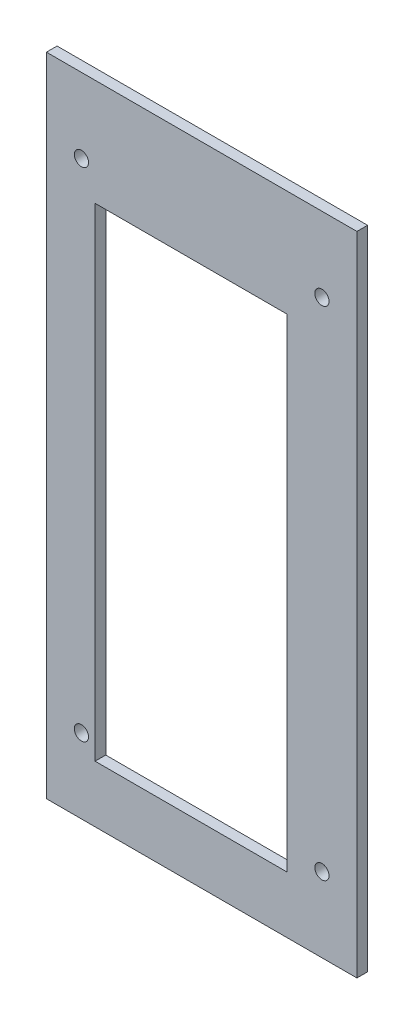
SolidWorks part; units mm, degrees
ref_plane "Front Plane" through (0, 0, 0) normal (0, 0, 1) x (1, 0, 0)
ref_plane "Top Plane" through (0, 0, 0) normal (0, 1, 0) x (1, 0, 0)
ref_plane "Right Plane" through (0, 0, 0) normal (1, 0, 0) x (0, 0, -1)
sketch "Sketch1" plane through (0, 0, 0) normal (0, 0, 1) x (1, 0, 0)
  line L0 (-16.925, 45.5) -> (-16.925, -45.5) construction
  line L1 (-21.85, 45.5) -> (21.85, 45.5)
  line L2 (-21.85, 45.5) -> (-21.85, -45.5)
  line L3 (-21.85, -45.5) -> (21.85, -45.5)
  line L4 (21.85, 45.5) -> (21.85, -45.5)
  line L5 (-21.85, 45.5) -> (21.85, -45.5) construction
  line L6 (-21.85, -45.5) -> (21.85, 45.5) construction
  line L7 (16.925, 45.5) -> (16.925, -45.5) construction
  line L8 (-15, 45.5) -> (-15, -45.5) construction
  line L9 (-15, 30.5) -> (12, 30.5)
  line L10 (-15, 30.5) -> (-15, -37.5)
  line L11 (-15, -37.5) -> (12, -37.5)
  line L12 (12, 30.5) -> (12, -37.5)
  line L13 (-18.85, -45.5) -> (-18.85, 45.5) construction
  line L14 (15, 45.5) -> (15, -45.5) construction
  line L15 (18.85, -45.5) -> (18.85, 45.5) construction
  line L16 (-21, 11.5) -> (21, 11.5) construction
  line L17 (-21.85, 0) -> (21.85, 0) construction
  line L18 (0, 45.5) -> (0, -45.5) construction
  circle A0 centre (16.925, 35) radius 1
  circle A1 centre (16.925, -35) radius 1
  circle A2 centre (-16.925, 35) radius 1
  circle A3 centre (-16.925, -35) radius 1
  point P0 (0, 0)
  dimension "D7" = 2
  dimension "D8" = 70
  dimension "D9" = 70
  dimension "D14" = 35
  dimension "D2" = 27
  dimension "D3" = 3
  dimension "D4" = 3
  dimension "D5" = 43.7
  dimension "D6" = 3
  dimension "D10" = 3.85
  dimension "D11" = 1.925
  dimension "D12" = 0
  dimension "5.65" = 3.85
  dimension "D13" = 1.925
  dimension "D15" = 19
  dimension "D16" = 49
  dimension "D17" = 15
  dimension "D18" = 10.5
  dimension "D20" = 91
extrude "Boss-Extrude1" add sketch "Sketch1" along normal blind 1.5
